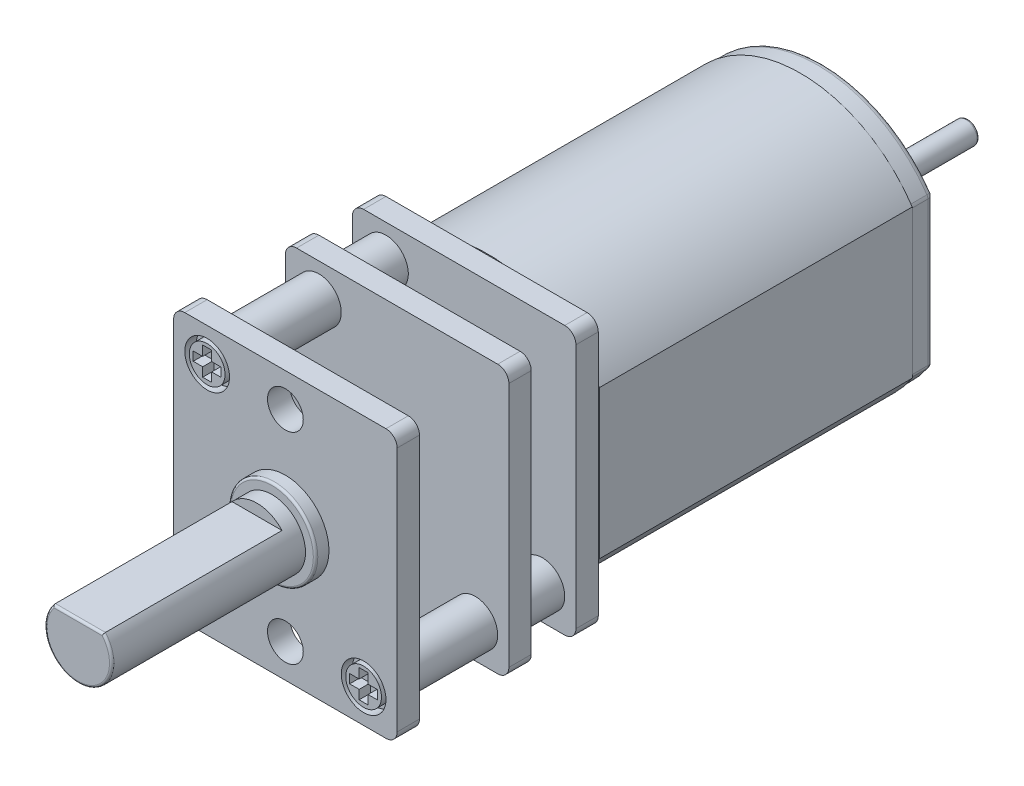
SolidWorks part; units mm, degrees
ref_plane "Plan de face" through (0, 0, 0) normal (0, 0, 1) x (1, 0, 0)
ref_plane "Plan de dessus" through (0, 0, 0) normal (0, 1, 0) x (1, 0, 0)
ref_plane "Plan de droite" through (0, 0, 0) normal (1, 0, 0) x (0, 0, -1)
sketch "Esquisse1" plane through (0, 0, 0) normal (0, 0, 1) x (1, 0, 0)
  line L0 (5, 3.3166) -> (5, -3.3166)
  line L1 (-5, 3.3166) -> (-5, -3.3166)
  arc A0 (5, 3.3166) -> (-5, 3.3166) centre (0, 0) ccw
  arc A1 (-5, -3.3166) -> (5, -3.3166) centre (0, 0) ccw
  dimension "D1" = 12
  dimension "D2" = 5
  dimension "D3" = 5
extrude "Boss.-Extru.1" add sketch "Esquisse1" along normal blind 14
sketch "Esquisse3" plane through (0, 0, 0) normal (0, 0, -1) x (-1, 0, 0)
  line L0 (-4.95, 3.3015) -> (-4.95, -3.3015)
  line L1 (4.95, 3.3015) -> (4.95, -3.3015)
  line L2 (-5, -3.3166) -> (-5, 3.3166) construction
  line L3 (5, 3.3166) -> (5, -3.3166) construction
  arc A0 (-4.95, 3.3015) -> (4.95, 3.3015) centre (0, 0) cw
  arc A1 (5, 3.3166) -> (-5, 3.3166) centre (0, 0) ccw construction
  arc A2 (-4.95, -3.3015) -> (4.95, -3.3015) centre (0, 0) ccw
  arc A3 (-5, -3.3166) -> (5, -3.3166) centre (0, 0) ccw construction
  dimension "D1" = 5.95
  dimension "D4" = 5.95
  dimension "D2" = 0.05
  dimension "D3" = 0.05
extrude "Boss.-Extru.3" add sketch "Esquisse3" along normal blind 1
sketch "Esquisse4" plane through (0, 0, -1) normal (0, 0, -1) x (-1, 0, 0)
  circle A0 centre (0, 0) radius 2.5
extrude "Boss.-Extru.4" add sketch "Esquisse4" along normal blind 2
sketch "Esquisse5" plane through (0, 0, -3) normal (0, 0, -1) x (-1, 0, 0)
  circle A0 centre (0, 0) radius 0.5
extrude "Boss.-Extru.5" add sketch "Esquisse5" along normal blind 4.5
sketch "Esquisse7" plane through (0, 0, 14) normal (0, 0, 1) x (1, 0, 0)
  line L1 (-4.5, 3) -> (4.5, 3)
  line L2 (-4.5, 3) -> (-4.5, -3)
  line L3 (-4.5, -3) -> (4.5, -3)
  line L4 (4.5, 3) -> (4.5, -3)
  dimension "D1" = 4.5
  dimension "D2" = 4.5
  dimension "D3" = 6
  dimension "D4" = 3
extrude "Boss.-Extru.7" add sketch "Esquisse7" along normal blind 0.05
sketch "Esquisse8" plane through (0, 0, 14.05) normal (0, 0, 1) x (1, 0, 0)
  line L0 (5, -3.3166) -> (5, 3.3166) construction
  line L1 (-4.5, 6) -> (4.5, 6)
  line L2 (-5, 5.5) -> (-5, -5.5)
  line L3 (-4.5, -6) -> (4.5, -6)
  line L4 (5, 5.5) -> (5, -5.5)
  line L5 (-5, 3.3166) -> (-5, -3.3166) construction
  arc A0 (5, 3.3166) -> (-5, 3.3166) centre (0, 0) ccw construction
  arc A1 (-5, -3.3166) -> (5, -3.3166) centre (0, 0) ccw construction
  arc A2 (4.5, 6) -> (5, 5.5) centre (4.5, 5.5) cw
  arc A3 (4.5, -6) -> (5, -5.5) centre (4.5, -5.5) ccw
  arc A4 (-5, -5.5) -> (-4.5, -6) centre (-4.5, -5.5) ccw
  arc A5 (-4.5, 6) -> (-5, 5.5) centre (-4.5, 5.5) ccw
  dimension "D1" = 0.5
extrude "Boss.-Extru.8" add sketch "Esquisse8" along normal blind 1
sketch "Esquisse9" plane through (0, 0, 15.05) normal (0, 0, 1) x (1, 0, 0)
  circle A0 centre (-3.5, 4.5) radius 1
  circle A1 centre (3.5, -4.5) radius 1
  dimension "D1" = 2
  dimension "D2" = 3.5
  dimension "D4" = 2
  dimension "D3" = 3.5
  dimension "D5" = 4.5
  dimension "D6" = 4.5
extrude "Boss.-Extru.9" add sketch "Esquisse9" along normal blind 2
sketch "Esquisse10" plane through (0, 0, 17.05) normal (0, 0, 1) x (1, 0, 0)
  line L0 (5, -5.5) -> (5, 5.5) construction
  line L1 (-4.5, 6) -> (4.5, 6)
  line L2 (-5, 5.5) -> (-5, -5.5)
  line L3 (-4.5, -6) -> (4.5, -6)
  line L4 (5, 5.5) -> (5, -5.5)
  line L5 (-5, 5.5) -> (-5, -5.5) construction
  line L6 (4.5, 6) -> (-4.5, 6) construction
  line L7 (-4.5, -6) -> (4.5, -6) construction
  arc A0 (-5, -5.5) -> (-4.5, -6) centre (-4.5, -5.5) ccw
  arc A1 (4.5, -6) -> (5, -5.5) centre (4.5, -5.5) ccw
  arc A2 (4.5, 6) -> (5, 5.5) centre (4.5, 5.5) cw
  arc A3 (-4.5, 6) -> (-5, 5.5) centre (-4.5, 5.5) ccw
  dimension "D1" = 0.5
extrude "Boss.-Extru.10" add sketch "Esquisse10" along normal blind 1
sketch "Esquisse11" plane through (0, 0, 18.05) normal (0, 0, 1) x (1, 0, 0)
  circle A0 centre (-3.5, 4.5) radius 1
  circle A1 centre (3.5, -4.5) radius 1
  dimension "D1" = 2
  dimension "D2" = 2
  dimension "D3" = 3.5
  dimension "D4" = 3.5
  dimension "D5" = 4.5
  dimension "D6" = 4.5
extrude "Boss.-Extru.11" add sketch "Esquisse11" along normal blind 4
sketch "Esquisse12" plane through (0, 0, 22.05) normal (0, 0, 1) x (1, 0, 0)
  line L0 (-5, 5.5) -> (-5, -5.5) construction
  line L1 (-4.5, 6) -> (4.5, 6)
  line L2 (-5, 5.5) -> (-5, -5.5)
  line L3 (-4.5, -6) -> (4.5, -6)
  line L4 (5, 5.5) -> (5, -5.5)
  line L5 (5, -5.5) -> (5, 5.5) construction
  line L6 (4.5, 6) -> (-4.5, 6) construction
  line L7 (-4.5, -6) -> (4.5, -6) construction
  arc A0 (-5, -5.5) -> (-4.5, -6) centre (-4.5, -5.5) ccw
  arc A1 (4.5, -6) -> (5, -5.5) centre (4.5, -5.5) ccw
  arc A2 (4.5, 6) -> (5, 5.5) centre (4.5, 5.5) cw
  arc A3 (-4.5, 6) -> (-5, 5.5) centre (-4.5, 5.5) ccw
  dimension "D1" = 0.5
extrude "Boss.-Extru.12" add sketch "Esquisse12" along normal blind 1
sketch "Esquisse13" plane through (0, 0, 23.05) normal (0, 0, 1) x (1, 0, 0)
  circle A0 centre (0, 4.5) radius 0.8
  circle A1 centre (0, -4.5) radius 0.8
  dimension "D1" = 1.6
  dimension "D2" = 1.6
  dimension "D3" = 4.5
  dimension "D4" = 4.5
extrude "Enlèv. mat.-Extru.1" cut sketch "Esquisse13" against normal blind 2
sketch "Esquisse14" plane through (0, 0, 23.05) normal (0, 0, 1) x (1, 0, 0)
  line L0 (-3.3, 4.7) -> (-2.875, 4.7)
  line L1 (-4.125, 4.7) -> (-3.7, 4.7)
  line L2 (-4.125, 4.7) -> (-4.125, 4.3)
  line L3 (-4.125, 4.3) -> (-3.7, 4.3)
  line L4 (-2.875, 4.7) -> (-2.875, 4.3)
  line L5 (-3.7, 5.1444) -> (-3.3, 5.1444)
  line L6 (-3.7, 5.1444) -> (-3.7, 4.7)
  line L7 (-3.7, 3.8944) -> (-3.3, 3.8944)
  line L8 (-3.3, 5.1444) -> (-3.3, 4.7)
  line L9 (-3.3, 4.3) -> (-3.3, 3.8944)
  line L10 (-3.3, 4.3) -> (-2.875, 4.3)
  line L11 (-3.7, 4.3) -> (-3.7, 3.8944)
  line L12 (4.125, -4.3) -> (4.125, -4.7)
  line L13 (2.875, -4.7) -> (3.3, -4.7)
  line L14 (2.875, -4.3) -> (2.875, -4.7)
  line L15 (3.3, -3.8556) -> (3.3, -4.3)
  line L16 (2.875, -4.3) -> (3.3, -4.3)
  line L17 (3.7, -3.8556) -> (3.7, -4.3)
  line L18 (3.7, -4.7) -> (4.125, -4.7)
  line L19 (3.7, -4.7) -> (3.7, -5.1056)
  line L20 (3.7, -4.3) -> (4.125, -4.3)
  line L21 (3.3, -4.7) -> (3.3, -5.1056)
  line L22 (3.3, -3.8556) -> (3.7, -3.8556)
  line L23 (3.3, -5.1056) -> (3.7, -5.1056)
  circle A0 centre (-3.5, 4.5) radius 1
  circle A1 centre (3.5, -4.5) radius 0.8
  circle A2 centre (-3.5, 4.5) radius 0.8
  circle A3 centre (3.5, -4.5) radius 1
  point P2 (0, 0)
  dimension "D3" = 2
  dimension "D4" = 2
  dimension "D5" = 1.6
  dimension "D6" = 0.4
  dimension "D1" = 3.5
  dimension "D2" = 4.5
  dimension "D7" = 0.4
  dimension "D8" = 0.4
  dimension "D9" = 0.2
  dimension "D10" = 0.2
  dimension "D11" = 0.625
  dimension "D12" = 1.25
  dimension "D13" = 1.25
  dimension "D14" = 0.2
  dimension "D15" = 0.2
  dimension "D16" = 0.625
  dimension "D17" = 1.25
  dimension "D18" = 1.25
  dimension "D19" = 4.5
  dimension "D20" = 3.5
extrude "Enlèv. mat.-Extru.2" cut sketch "Esquisse14" against normal blind 0.5 contours A0 A2 | L3 L11 L7 L9 L10 L4 L0 L8 L5 L6 L1 L2 | L21 L23 L19 L18 L12 L20 L17 L22 L15 L16 L14 L13 | A3 A1
sketch "Esquisse15" plane through (0, 0, 23.05) normal (0, 0, 1) x (1, 0, 0)
  circle A0 centre (0, 0) radius 1.95
  dimension "D1" = 3.9
extrude "Boss.-Extru.13" add sketch "Esquisse15" along normal blind 0.6
sketch "Esquisse16" plane through (0, 0, 23.65) normal (0, 0, 1) x (1, 0, 0)
  circle A0 centre (0, 0) radius 1.5
extrude "Boss.-Extru.14" add sketch "Esquisse16" along normal blind 8.67
sketch "Esquisse17" plane through (0, 0, 32.32) normal (0, 0, 1) x (1, 0, 0)
  line L0 (-1.118, 1) -> (1.118, 1)
  arc A0 (-1.118, 1) -> (1.118, 1) centre (0, 0) cw
  circle A1 centre (0, 0) radius 1.5 construction
  dimension "D1" = 1
extrude "Enlèv. mat.-Extru.3" cut sketch "Esquisse17" against normal blind 8
fillet "Congé1" radius 0.25 7 edges at (0, -5.95, -1) (2.5, 0, -1) (-4.95, 0, -1) (-2.5, 0, -3) (4.95, 3.3015, -0.5) (4.95, 0, -1) (0, 5.95, -1)
fillet "Congé2" radius 0.1 1 edges at (-0.5, 0, -7.5)
fillet "Congé3" radius 0.1 2 edges at (0, 1, 32.32) (0, -1.5, 32.32)
fillet "Congé4" radius 0.1 1 edges at (1.95, 0, 23.65)
fillet "Congé5" radius 0.25 6 edges at (4.8992, -3.2861, -0.9011) (-4.95, 3.3015, -0.375) (-4.8992, 3.2861, -0.9011) (-4.8992, -3.2861, -0.9011) (-4.95, -3.3015, -0.375) (4.95, -3.3015, -0.375)
